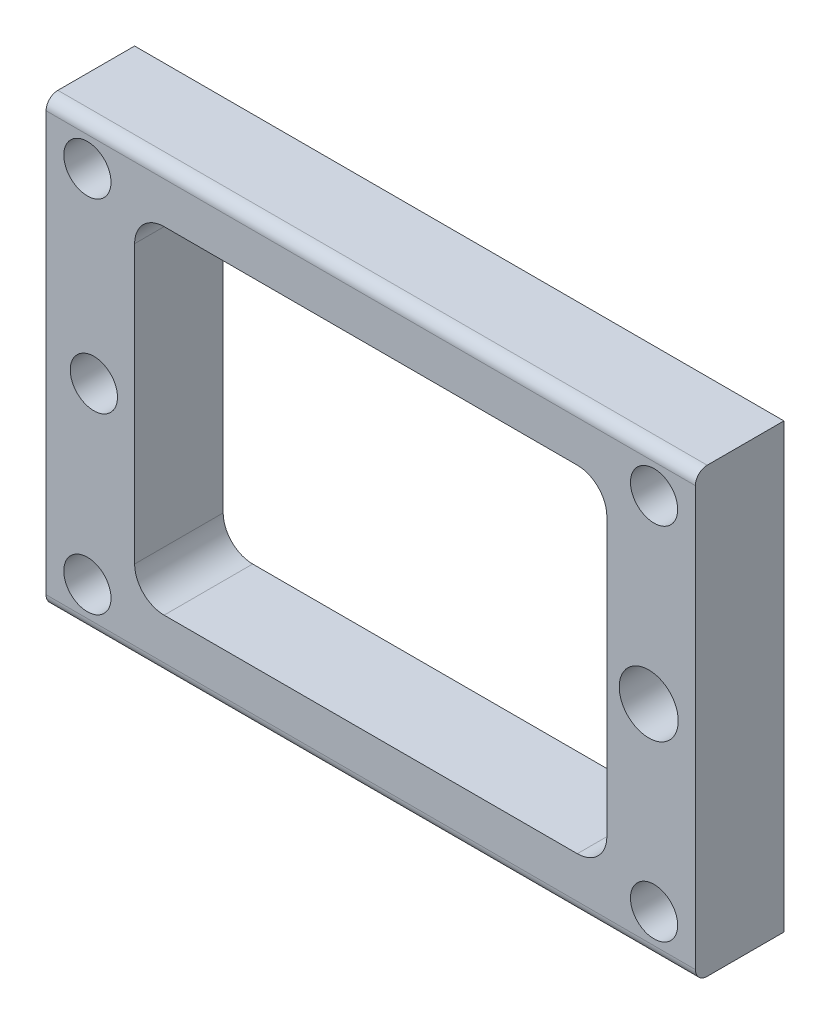
SolidWorks part; units mm, degrees
ref_plane "Front Plane" through (0, 0, 0) normal (0, 0, 1) x (1, 0, 0)
ref_plane "Top Plane" through (0, 0, 0) normal (0, 1, 0) x (1, 0, 0)
ref_plane "Right Plane" through (0, 0, 0) normal (1, 0, 0) x (0, 0, -1)
sketch "Croquis2" plane through (0, 0, 0) normal (0, 0, 1) x (1, 0, 0)
  line L8 (-638.8623, 859.0574) -> (-638.8623, 934.0574)
  line L9 (-638.8623, 934.0574) -> (-748.8623, 934.0574)
  line L10 (-748.8623, 934.0574) -> (-748.8623, 859.0574)
  line L11 (-748.8623, 859.0574) -> (-638.8623, 859.0574)
  line L76 (-706.3623, 925.0574) -> (-728.8623, 925.0574)
  line L77 (-681.3623, 925.0574) -> (-706.3623, 925.0574)
  line L78 (-658.8623, 925.0574) -> (-681.3623, 925.0574)
  line L79 (-653.8623, 873.0574) -> (-653.8623, 920.0574)
  line L80 (-681.3623, 868.0574) -> (-658.8623, 868.0574)
  line L81 (-706.3623, 868.0574) -> (-681.3623, 868.0574)
  line L82 (-728.8623, 868.0574) -> (-706.3623, 868.0574)
  line L83 (-733.8623, 920.0574) -> (-733.8623, 873.0574)
  circle A48 centre (-645.8623, 927.0574) radius 1.9975
  circle A49 centre (-741.8623, 927.0574) radius 2
  circle A50 centre (-741.8623, 866.0574) radius 2
  circle A51 centre (-645.8623, 866.0574) radius 2
  arc A52 (-653.8623, 920.0574) -> (-658.8623, 925.0574) centre (-658.8623, 920.0574) ccw
  arc A53 (-658.8623, 868.0574) -> (-653.8623, 873.0574) centre (-658.8623, 873.0574) ccw
  arc A54 (-733.8623, 873.0574) -> (-728.8623, 868.0574) centre (-728.8623, 873.0574) ccw
  arc A55 (-728.8623, 925.0574) -> (-733.8623, 920.0574) centre (-728.8623, 920.0574) ccw
  dimension "D1" = 3.995
  dimension "D2" = 4
  dimension "D4" = 4
  dimension "D5" = 4
  dimension "D6" = 7
  dimension "D7" = 7
  dimension "D8" = 7
  dimension "D9" = 7
  dimension "D10" = 7
  dimension "D12" = 7
  dimension "D13" = 7
  dimension "D11" = 7
extrude "Saliente-Extruir1" add sketch "Croquis2" along normal blind 15
sketch "Croquis3" plane through (0, 0, 15) normal (0, 0, 1) x (1, 0, 0)
  circle A0 centre (-645.8623, 927.0574) radius 4
  circle A1 centre (-645.8623, 866.0574) radius 4
  circle A2 centre (-741.8623, 866.0574) radius 4
  circle A3 centre (-741.8623, 927.0574) radius 4
  dimension "D1" = 8
extrude "Cortar-Extruir1" cut sketch "Croquis3" against normal blind 6
fillet "Redondeo2" radius 2 2 edges at (-693.8623, 859.0574, 15) (-693.8623, 934.0574, 15)
sketch "Croquis4" plane through (0, 0, 15) normal (0, 0, 1) x (1, 0, 0)
  circle A0 centre (-736.8623, 896.5574) radius 3.5
  circle A1 centre (-642.8623, 896.5574) radius 3
  dimension "D1" = 7
  dimension "D2" = 6
extrude "Cortar-Extruir8" cut sketch "Croquis4" against normal blind 15
sketch "Croquis5" plane through (0, 0, 15) normal (0, 0, 1) x (1, 0, 0)
  line L0 (-733.8623, 893.7892) -> (-733.8623, 899.3255)
  circle A0 centre (-642.8623, 896.5574) radius 3.7015
  arc A1 (-733.8623, 899.3255) -> (-733.8623, 893.7892) centre (-736.8623, 896.5574) ccw
extrude "Saliente-Extruir2" add sketch "Croquis5" against normal up to surface (15 mm away) up to face at (-639.8623, 896.5574, 0)
sketch "Croquis7" plane through (0, 0, 15) normal (0, 0, 1) x (1, 0, 0)
  circle A0 centre (-740.7664, 896.0847) radius 4
  circle A1 centre (-646.7664, 896.0847) radius 5
  dimension "D1" = 8
  dimension "D2" = 10
extrude "Cortar-Extruir9" cut sketch "Croquis7" against normal up to surface (15 mm away) up to face at (-693.8623, 896.5574, 0)
